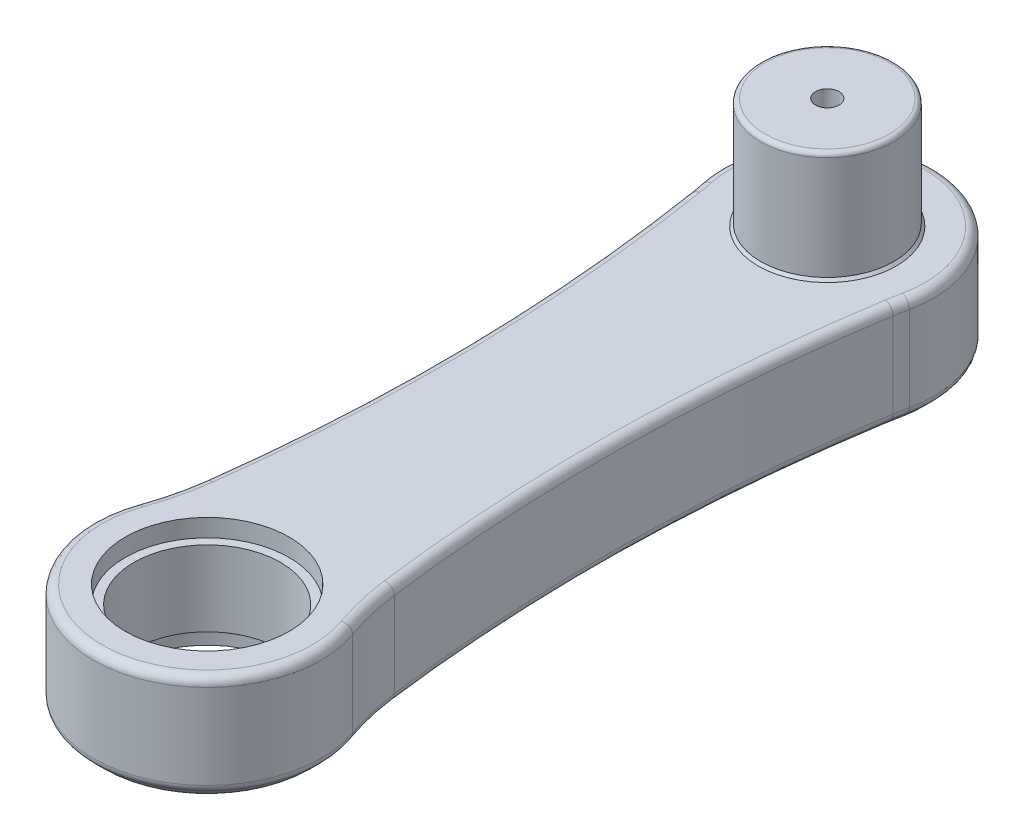
SolidWorks part; units mm, degrees
ref_plane "Front Plane" through (0, 0, 0) normal (0, 0, 1) x (1, 0, 0)
ref_plane "Top Plane" through (0, 0, 0) normal (0, 1, 0) x (1, 0, 0)
ref_plane "Right Plane" through (0, 0, 0) normal (1, 0, 0) x (0, 0, -1)
sketch "Sketch1" plane through (0, 0, 0) normal (0, 1, 0) x (1, 0, 0)
  line L0 (0, 70) -> (0, -70)
  arc A2 (-22.9728, 61.8599) -> (-21.3211, -49.0771) centre (-407.7275, 0.6504) cw
  arc A3 (22.9728, 61.8599) -> (21.3211, -49.0771) centre (407.7275, 0.6504) ccw
  arc A4 (-23.5517, 64.9685) -> (23.5517, 64.9685) centre (0, 70) cw
  arc A5 (-24.2625, -61.4209) -> (24.2625, -61.4209) centre (0, -70) ccw
  arc A6 (-24, 68) -> (24, 68) centre (0, 70) cw
  arc A7 (-22.5, -57.5092) -> (22.5, -57.5092) centre (0, -70) ccw
  arc A8 (-23.5517, 64.9685) -> (-22.9728, 61.8599) centre (-82.2277, 52.4332) cw
  arc A9 (23.5517, 64.9685) -> (22.9728, 61.8599) centre (82.2277, 52.4332) ccw
  arc A10 (24.2625, -61.4209) -> (21.3211, -49.0771) centre (80.8303, -41.4187) cw
  arc A11 (-21.3211, -49.0771) -> (-24.2625, -61.4209) centre (-80.8303, -41.4187) cw
  point P4 (0, 0)
  point P10 (0, 68)
  dimension "D2" = 60
  dimension "D3" = 0
  dimension "D7" = 48.525
  dimension "D1" = 140
  dimension "D4" = 48
  dimension "D5" = 45
  dimension "D6" = 0
extrude "Boss-Extrude1" add sketch "Sketch1" along normal blind 25
fillet "Fillet1" radius 2 8 edges at (23.2418, 25, -63.418) (0, 25, -94.0832) (-23.2418, 25, -63.418) (-18.1776, 25, -6.4505) (-22.4645, 25, 55.327) (0, 25, 95.7346) (22.4645, 25, 55.327) (18.1776, 25, -6.4505)
chamfer "Chamfer1" distance 3 angle 45 8 edges at (0, 0, -94.0832) (-23.2418, 0, -63.418) (23.2418, 0, -63.418) (-18.1776, 0, -6.4505) (18.1776, 0, -6.4505) (-22.4645, 0, 55.327) (22.4645, 0, 55.327) (0, 0, 95.7346)
fillet "Fillet2" radius 2 16 edges at (-22.4645, 3, 55.327) (-18.1776, 3, -6.4505) (-23.2418, 3, -63.418) (0, 3, -94.0832) (23.2418, 3, -63.418) (18.1776, 3, -6.4505) (22.4645, 3, 55.327) (19.5463, 0, 56.0224) (15.1779, 0, -6.4952) (20.2925, 0, -63.9673) (0, 0, -91.0832) (-20.2925, 0, -63.9673) (-15.1779, 0, -6.4952) (-19.5463, 0, 56.0224) (0, 3, 95.7346) (0, 0, 92.7346)
sketch "Sketch2" plane through (0, 25, 0) normal (0, 1, 0) x (1, 0, 0)
  circle A1 centre (0, -70) radius 18.485
  dimension "D2" = 36.97
extrude "Cut-Extrude1" cut sketch "Sketch2" against normal blind 4
sketch "Sketch3" plane through (0, 0, 0) normal (0, -1, 0) x (1, 0, 0)
  circle A0 centre (0, 70) radius 18.485
  dimension "D1" = 36.97
extrude "Cut-Extrude2" cut sketch "Sketch3" against normal blind 4
sketch "Sketch4" plane through (0, 4, 0) normal (0, -1, 0) x (1, 0, 0)
  circle A0 centre (0, 70) radius 16.55
  dimension "D1" = 33.1
extrude "Cut-Extrude3" cut sketch "Sketch4" against normal blind 17
sketch "Sketch5" plane through (0, 25, 0) normal (0, 1, 0) x (1, 0, 0)
  circle A0 centre (0, 70) radius 15.01
  dimension "D1" = 30.02
extrude "Boss-Extrude2" add sketch "Sketch5" along normal blind 25
chamfer "Chamfer2" distance 0.58 angle 45 1 edges at (0, 25, -54.99)
sketch "Sketch6" plane through (0, 50, 0) normal (0, 1, 0) x (1, 0, 0)
  circle A0 centre (0, 70) radius 2.65
  dimension "D1" = 5.3
extrude "Cut-Extrude4" cut sketch "Sketch6" against normal blind 50
sketch "Sketch7" plane through (0, 0, 0) normal (0, -1, 0) x (1, 0, 0)
  circle A0 centre (0, -70) radius 3
  dimension "D1" = 6
extrude "Cut-Extrude5" cut sketch "Sketch7" against normal blind 8
fillet "Fillet3" radius 1 1 edges at (0, 50, -54.99)
